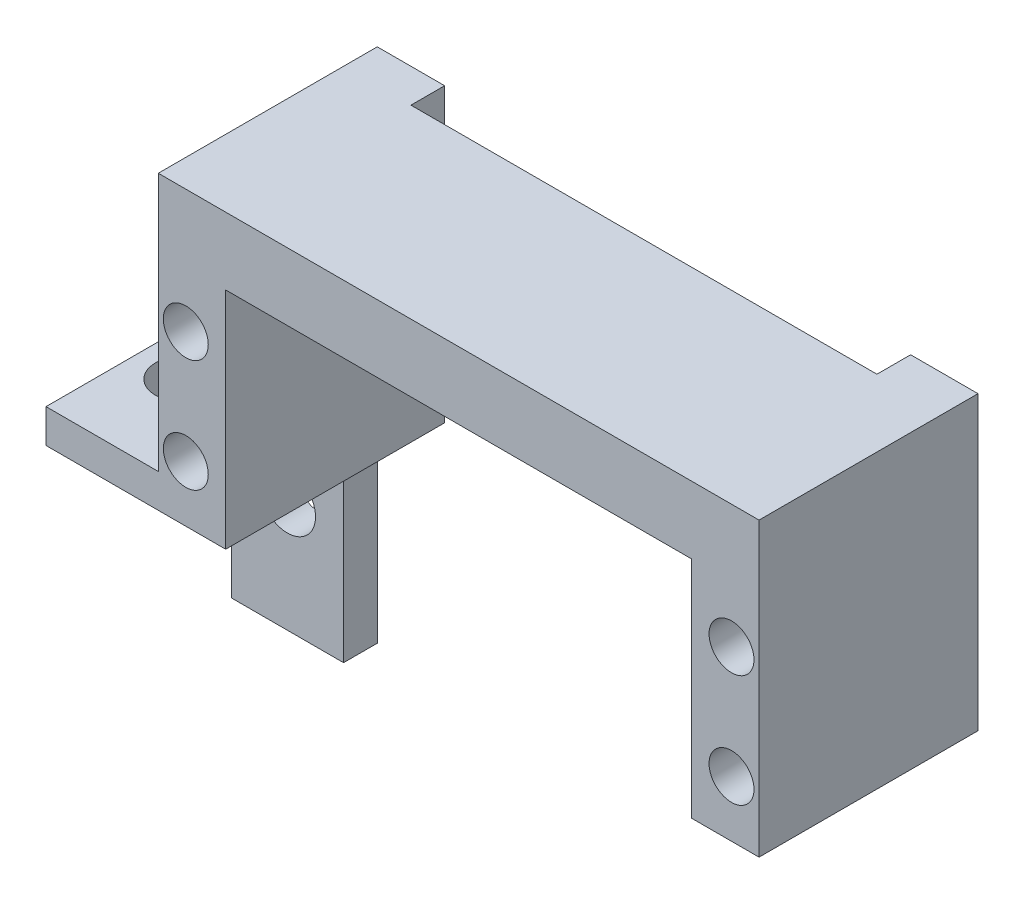
SolidWorks part; units mm, degrees
ref_plane "前视基准面" through (0, 0, 0) normal (0, 0, 1) x (1, 0, 0)
ref_plane "上视基准面" through (0, 0, 0) normal (0, 1, 0) x (1, 0, 0)
ref_plane "右视基准面" through (0, 0, 0) normal (1, 0, 0) x (0, 0, -1)
sketch "草图1" plane through (0, 0, 0) normal (0, 0, 1) x (1, 0, 0)
  line L0 (0, 38.2514) -> (0, 0) construction
  line L1 (0, 0) -> (26.75, 0)
  line L2 (26.75, 0) -> (26.75, -20)
  line L3 (26.75, -20) -> (36.75, -20)
  line L4 (0, -6) -> (20.75, -6)
  line L5 (20.75, -6) -> (20.75, -26)
  line L6 (20.75, -26) -> (36.75, -26)
  line L7 (-36.75, -20) -> (-36.75, -26)
  line L8 (36.75, -20) -> (36.75, -26)
  line L9 (-20.75, -26) -> (-36.75, -26)
  line L10 (-20.75, -6) -> (-20.75, -26)
  line L11 (0, -6) -> (-20.75, -6)
  line L12 (-26.75, -20) -> (-36.75, -20)
  line L13 (-26.75, 0) -> (-26.75, -20)
  line L14 (0, 0) -> (-26.75, 0)
  dimension "D2" = 41.5
  dimension "D3" = 20
  dimension "D4" = 10
  dimension "D5" = 0
  dimension "D1" = 6
extrude "凸台-拉伸1" add sketch "草图1" along normal blind 16.5
sketch "草图2" plane through (0, -20, 0) normal (0, 1, 0) x (1, 0, 0)
  line L0 (36.75, -16.5) -> (26.75, -16.5) construction
  line L1 (36.75, -16.5) -> (36.75, 0) construction
  circle A0 centre (32.75, -8.25) radius 2.5
  dimension "D1" = 5
  dimension "D2" = 8.25
  dimension "D3" = 4
extrude "切除-拉伸1" cut sketch "草图2" against normal blind 16.5
sketch "草图3" plane through (0, -20, 0) normal (0, 1, 0) x (1, 0, 0)
  line L1 (36.75, 0) -> (26.75, 0)
  line L2 (36.75, 0) -> (36.75, -16.5)
  line L3 (36.75, -16.5) -> (26.75, -16.5)
  line L4 (26.75, 0) -> (26.75, -16.5)
extrude "切除-拉伸2" cut sketch "草图3" against normal blind 3
sketch "草图4" plane through (0, 0, 16.5) normal (0, 0, 1) x (1, 0, 0)
  line L2 (-26.75, 0) -> (-38.6463, 0)
  line L3 (-26.75, 0) -> (-26.75, -29.0846)
  line L4 (-26.75, -29.0846) -> (-38.6463, -29.0846)
  line L5 (-38.6463, 0) -> (-38.6463, -29.0846)
extrude "切除-拉伸3" cut sketch "草图4" against normal through all
sketch "草图5" plane through (0, 0, 0) normal (0, 0, -1) x (-1, 0, 0)
  line L0 (20.75, -16) -> (-20.75, -16) construction
  line L1 (20.75, -26) -> (20.75, -6) construction
  line L2 (-20.75, -6) -> (-20.75, -26) construction
  line L3 (0, 0) -> (0, -37.9358) construction
  line L4 (-26.75, 0) -> (26.75, 0) construction
  circle A0 centre (-24.3, -11) radius 2
  circle A1 centre (-24.3, -21) radius 2
  circle A2 centre (24.3, -21) radius 2
  circle A3 centre (24.3, -11) radius 2
  dimension "D1" = 4
  dimension "D2" = 4
  dimension "D3" = 10
  dimension "D4" = 5
  dimension "D5" = 24.3
  dimension "D6" = 24.3
extrude "切除-拉伸4" cut sketch "草图5" against normal through all
sketch "草图6" plane through (0, 0, 0) normal (0, 0, -1) x (-1, 0, 0)
  line L1 (-26.75, -23) -> (-36.75, -23)
  line L2 (-26.75, -23) -> (-26.75, -46)
  line L3 (-26.75, -46) -> (-36.75, -46)
  line L4 (-36.75, -23) -> (-36.75, -46)
  dimension "D1" = 23
extrude "凸台-拉伸2" add sketch "草图6" along normal blind 3
sketch "草图7" plane through (0, 0, -3) normal (0, 0, -1) x (-1, 0, 0)
  line L0 (-36.75, -46) -> (-26.75, -46) construction
  line L1 (-36.75, -23) -> (-36.75, -46) construction
  circle A0 centre (-31.75, -36) radius 2.5
  dimension "D1" = 5
  dimension "D2" = 10
  dimension "D3" = 5
extrude "切除-拉伸5" cut sketch "草图7" against normal blind 3
sketch "草图8" plane through (0, 0, 0) normal (0, 0, -1) x (-1, 0, 0)
  line L0 (-36.75, -46) -> (-26.75, -46) construction
  line L1 (26.75, 0) -> (20.75, 0)
  line L2 (26.75, 0) -> (26.75, -26)
  line L3 (26.75, -46) -> (20.75, -46)
  line L4 (20.75, 0) -> (20.75, -46)
  line L6 (26.75, -46) -> (30.75, -46)
  line L8 (26.75, -26) -> (30.75, -26)
  line L9 (30.75, -46) -> (30.75, -26)
  line L11 (-20.75, -26) -> (-26.75, -26)
  line L12 (-20.75, -26) -> (-20.75, 0)
  line L13 (-20.75, 0) -> (-26.75, 0)
  line L14 (-26.75, -26) -> (-26.75, 0)
  circle A0 centre (24.3, -21) radius 2 construction
  circle A1 centre (24.3, -21) radius 2
  circle A2 centre (24.3, -11) radius 2 construction
  circle A3 centre (24.3, -11) radius 2
  circle A4 centre (-24.3, -11) radius 2 construction
  circle A5 centre (-24.3, -21) radius 2 construction
  circle A6 centre (-24.3, -11) radius 2
  circle A7 centre (-24.3, -21) radius 2
  dimension "D1" = 6
  dimension "D2" = 20
  dimension "D3" = 10
extrude "凸台-拉伸3" add sketch "草图8" along normal blind 3
sketch "草图9" plane through (0, 0, -3) normal (0, 0, -1) x (-1, 0, 0)
  line L0 (30.75, -46) -> (30.75, -26) construction
  line L1 (20.75, -46) -> (30.75, -46) construction
  circle A0 centre (25.75, -36) radius 2.5
  dimension "D1" = 5
  dimension "D2" = 5
  dimension "D3" = 10
extrude "切除-拉伸6" cut sketch "草图9" against normal blind 3
mirror "镜向1" about plane through (36.75, -20, 16.5) normal (-1, 0, 0) of bodies 114
sketch "草图10" plane through (0, 0, -3) normal (0, 0, -1) x (-1, 0, 0)
  line L0 (-46.75, -46) -> (-26.75, -46) construction
  line L1 (-36.75, -46) -> (37.944, -46)
  line L2 (-36.75, -46) -> (-36.75, 6.0951)
  line L3 (-36.75, 6.0951) -> (37.944, 6.0951)
  line L4 (37.944, -46) -> (37.944, 6.0951)
extrude "切除-拉伸7" cut sketch "草图10" against normal through all
sketch "草图11" plane through (0, 0, -3) normal (0, 0, -1) x (-1, 0, 0)
  line L1 (-94.25, -26) -> (-110.7326, -26)
  line L2 (-94.25, -26) -> (-94.25, -51.8105)
  line L3 (-94.25, -51.8105) -> (-110.7326, -51.8105)
  line L4 (-110.7326, -26) -> (-110.7326, -51.8105)
extrude "切除-拉伸8" cut sketch "草图11" against normal blind 10 contours L3 L4 L1 L2
